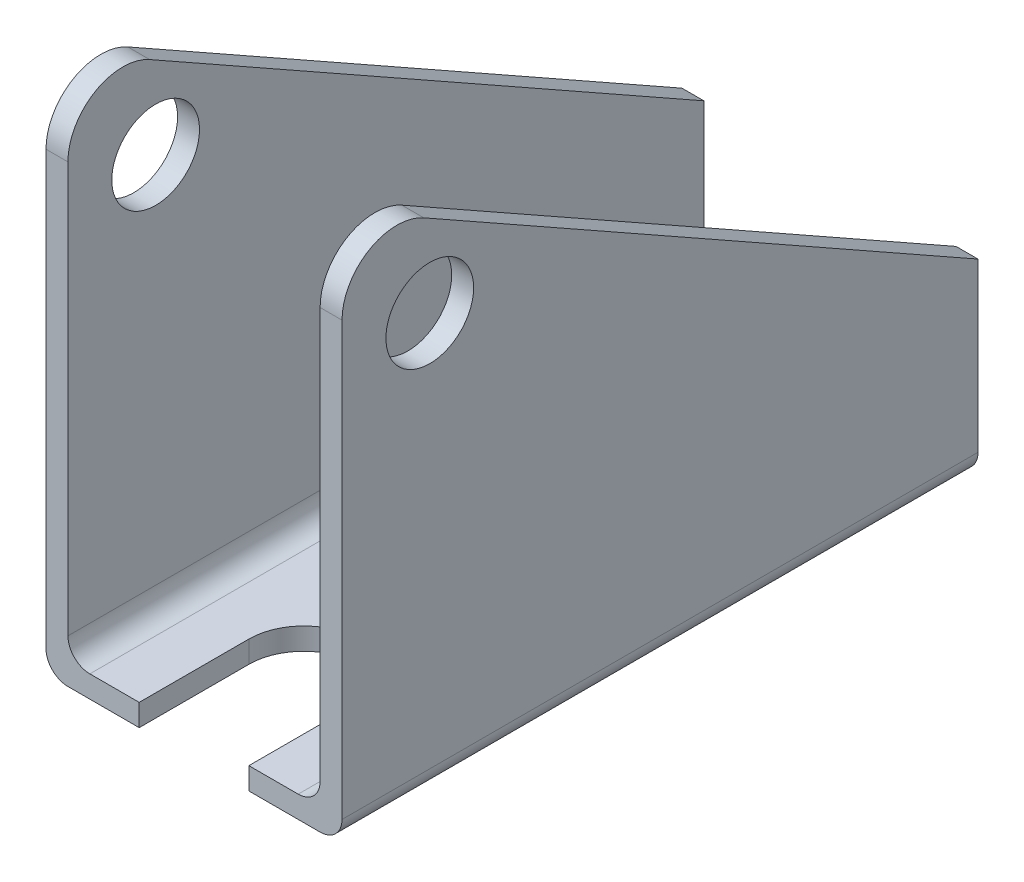
SolidWorks part; units mm, degrees
ref_plane "Front Plane" through (0, 0, 0) normal (0, 0, 1) x (1, 0, 0)
ref_plane "Top Plane" through (0, 0, 0) normal (0, 1, 0) x (1, 0, 0)
ref_plane "Right Plane" through (0, 0, 0) normal (1, 0, 0) x (0, 0, -1)
sketch "Sketch1" plane through (0, 0, 0) normal (0, 1, 0) x (1, 0, 0)
  line L1 (-13.5, 29) -> (13.5, 29)
  line L2 (-13.5, 29) -> (-13.5, -29)
  line L3 (-13.5, -29) -> (13.5, -29)
  line L4 (13.5, 29) -> (13.5, -29)
  line L5 (-13.5, 29) -> (13.5, -29) construction
  line L6 (-13.5, -29) -> (13.5, 29) construction
  point P0 (0, 0)
  dimension "D1" = 58
  dimension "D2" = 27
extrude "Boss-Extrude1" add sketch "Sketch1" along normal blind 2
sketch "Sketch2" plane through (0, 0, 29) normal (0, 0, 1) x (1, 0, 0)
  line L0 (-13.5, 2) -> (-13.5, 50)
  line L1 (-13.5, 50) -> (-11.5, 50)
  line L2 (-11.5, 50) -> (-11.5, 4)
  line L3 (-13.5, 2) -> (13.5, 2) construction
  line L4 (13.5, 2) -> (13.5, 50)
  line L5 (13.5, 50) -> (11.5, 50)
  line L6 (11.5, 50) -> (11.5, 4)
  line L7 (9.5, 2) -> (-9.5, 2)
  line L8 (-11.5, 0) -> (11.5, 0)
  arc A0 (11.5, 4) -> (9.5, 2) centre (9.5, 4) cw
  arc A1 (-11.5, 4) -> (-9.5, 2) centre (-9.5, 4) ccw
  arc A2 (13.5, 2) -> (11.5, 0) centre (11.5, 2) cw
  arc A3 (-13.5, 2) -> (-11.5, 0) centre (-11.5, 2) ccw
  point P14 (11.5, 2)
  point P17 (-11.5, 2)
  point P20 (13.5, 0)
  point P23 (-13.5, 0)
  dimension "D5" = 2
  dimension "D1" = 50
  dimension "D2" = 50
  dimension "D3" = 2
  dimension "D4" = 2
extrude "Boss-Extrude2" add sketch "Sketch2" against normal blind 58
sketch "Sketch3" plane through (13.5, 0, 0) normal (1, 0, 0) x (0, 0, -1)
  line L1 (29, 50) -> (29, 0) construction
  line L2 (29, 17.2617) -> (-29, 50)
  line L3 (-29, 50) -> (29, 50)
  line L4 (29, 50) -> (29, 17.2617)
extrude "Cut-Extrude1" cut sketch "Sketch3" against normal blind 58
sketch "Sketch4" plane through (13.5, 0, 0) normal (1, 0, 0) x (0, 0, -1)
  line L0 (-29, 0) -> (-29, 38) construction
  line L1 (-29, 50) -> (-29, 0) construction
  line L2 (-29, 0) -> (29, 0) construction
  line L3 (-29, 38) -> (-21, 38) construction
  circle A0 centre (-21, 38) radius 4
  dimension "D3" = 8
  dimension "D1" = 38
  dimension "D2" = 8
extrude "Cut-Extrude2" cut sketch "Sketch4" against normal blind 58
sketch "Sketch5" plane through (13.5, 0, 0) normal (1, 0, 0) x (0, 0, -1)
  line L2 (-29, 41.4362) -> (-29, 50)
  line L3 (-29, 50) -> (-21.5422, 45.7904)
  arc A0 (-21.5422, 45.7904) -> (-29, 41.4362) centre (-24, 41.4362) ccw
  dimension "D1" = 5
extrude "Cut-Extrude3" cut sketch "Sketch5" against normal blind 58
sketch "Sketch6" plane through (0, 0, 29) normal (0, 0, 1) x (1, 0, 0)
  line L0 (-13.5, 0) -> (13.5, 0) construction
  line L1 (13.5, 41.4362) -> (13.5, 0) construction
  line L2 (-13.5, 41.4362) -> (-13.5, 0) construction
  line L3 (-13.5, 0) -> (-11.5, 0)
  line L4 (13.5, 2) -> (13.5, 0)
  line L5 (-13.5, 2) -> (-13.5, 0)
  line L6 (11.5, 0) -> (13.5, 0)
  arc A0 (11.5, 0) -> (13.5, 2) centre (11.5, 2) ccw construction
  arc A1 (-13.5, 2) -> (-11.5, 0) centre (-11.5, 2) ccw construction
  arc A2 (11.5, 0) -> (13.5, 2) centre (11.5, 2) ccw
  arc A3 (-13.5, 2) -> (-11.5, 0) centre (-11.5, 2) ccw
extrude "Cut-Extrude4" cut sketch "Sketch6" against normal blind 58
sketch "Sketch7" plane through (0, 0, 0) normal (0, -1, 0) x (1, 0, 0)
  line L0 (0, -29) -> (0, -11) construction
  line L1 (11.5, -29) -> (-11.5, -29) construction
  line L2 (0, -11) -> (0, 19) construction
  line L3 (-5, 19) -> (-5, 29)
  line L4 (-11.5, 29) -> (11.5, 29) construction
  line L5 (5, 19) -> (5, 29)
  line L6 (5, 29) -> (-5, 29)
  arc A0 (-5, 19) -> (5, 19) centre (0, 19) ccw
  circle A1 centre (0, -11) radius 5
  dimension "D3" = 10
  dimension "D4" = 10
  dimension "D1" = 18
  dimension "D2" = 30
extrude "Cut-Extrude5" cut sketch "Sketch7" against normal blind 58
